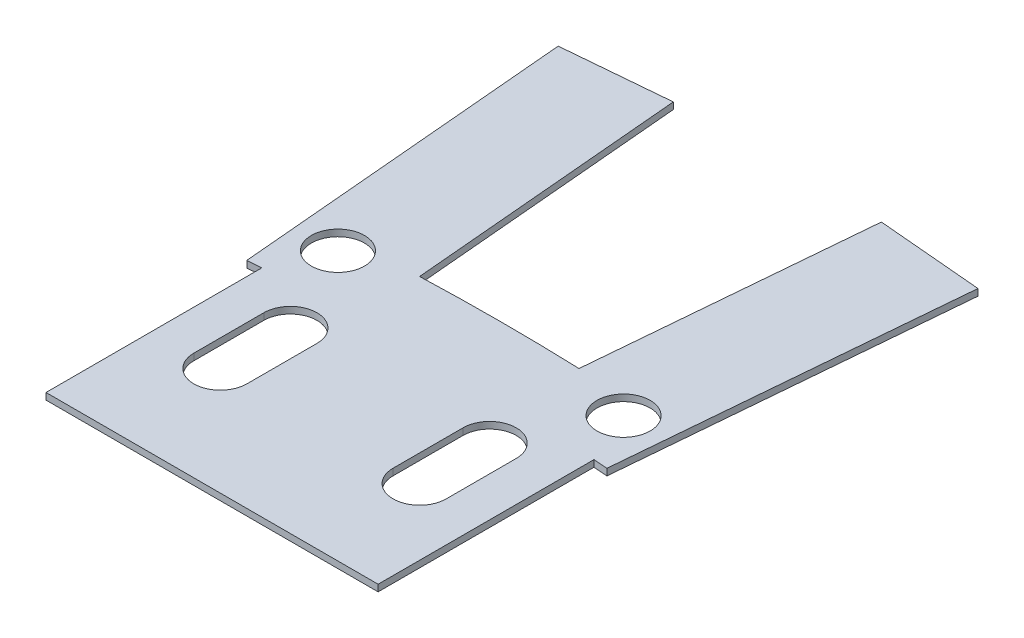
SolidWorks part; units mm, degrees
material "Galvanized Steel"
ref_plane "Front Plane" through (0, 0, 0) normal (0, 0, 1) x (1, 0, 0)
ref_plane "Top Plane" through (0, 0, 0) normal (0, 1, 0) x (1, 0, 0)
ref_plane "Right Plane" through (0, 0, 0) normal (1, 0, 0) x (0, 0, -1)
sketch "Sketch1" plane through (0, 0, 0) normal (0, 1, 0) x (1, 0, 0)
  line L0 (-1000, 0) -> (49000, 0) construction
  line L1 (0, -1000) -> (0, 49000) construction
  line L2 (-500, -866.0254) -> (24500, 42435.2448) construction
  line L3 (-500, 866.0254) -> (24500, -42435.2448) construction
  line L7 (25, 325.8046) -> (25, 293.3046)
  line L8 (25, 293.3046) -> (-25, 293.3046)
  line L9 (27.1064, 325.6361) -> (27.947, 335.244)
  line L10 (-25, 325.8046) -> (-25, 293.3046)
  line L11 (27.947, 335.244) -> (31.6015, 377.0151)
  line L12 (31.6015, 377.0151) -> (15.6624, 378.4096)
  line L13 (15.6624, 378.4096) -> (12, 336.5485)
  line L14 (-15.6624, 378.4096) -> (-12, 336.5485)
  line L15 (-31.6015, 377.0151) -> (-15.6624, 378.4096)
  line L16 (-27.947, 335.244) -> (-31.6015, 377.0151)
  line L17 (-27.1064, 325.6361) -> (-27.947, 335.244)
  line L18 (-19, 320.0981) -> (-19, 309.5546)
  line L20 (-11, 320.0981) -> (-11, 309.5546)
  line L21 (19, 320.0981) -> (19, 309.5546)
  line L22 (11, 320.0981) -> (11, 309.5546)
  circle A0 centre (0, 0) radius 400 construction
  arc A14 (25, 325.8046) -> (27.1064, 325.6361) centre (0, 0) cw
  arc A15 (-25, 325.8046) -> (-27.1064, 325.6361) centre (0, 0) ccw
  arc A16 (12, 336.5485) -> (-12, 336.5485) centre (0, 0) ccw
  arc A17 (-19, 309.5546) -> (-11, 309.5546) centre (-15, 309.5546) ccw
  circle A19 centre (-21.5, 333.7549) radius 4
  circle A20 centre (21.5, 333.7549) radius 4
  arc A21 (-11, 320.0981) -> (-19, 320.0981) centre (-15, 320.0981) ccw
  arc A22 (19, 309.5546) -> (11, 309.5546) centre (15, 309.5546) cw
  arc A23 (11, 320.0981) -> (19, 320.0981) centre (15, 320.0981) cw
  point P34 (0, 293.3046)
  dimension "D1" = 800
  dimension "D4" = 5
  dimension "D5" = 24
  dimension "D8" = 10
  dimension "D9" = 50
  dimension "D12" = 16.25
  dimension "D13" = 30
  dimension "D14" = 21.5
  dimension "D15" = 8
  dimension "D6" = 16
  dimension "D7" = 336.7623
  dimension "D10" = 8
  dimension "D17" = 8
  dimension "D2" = 60
  dimension "D3" = 60
  dimension "D11" = 32.5
  dimension "D16" = 42.021
extrude "Boss-Extrude1" add sketch "Sketch1" along normal mid plane 1
